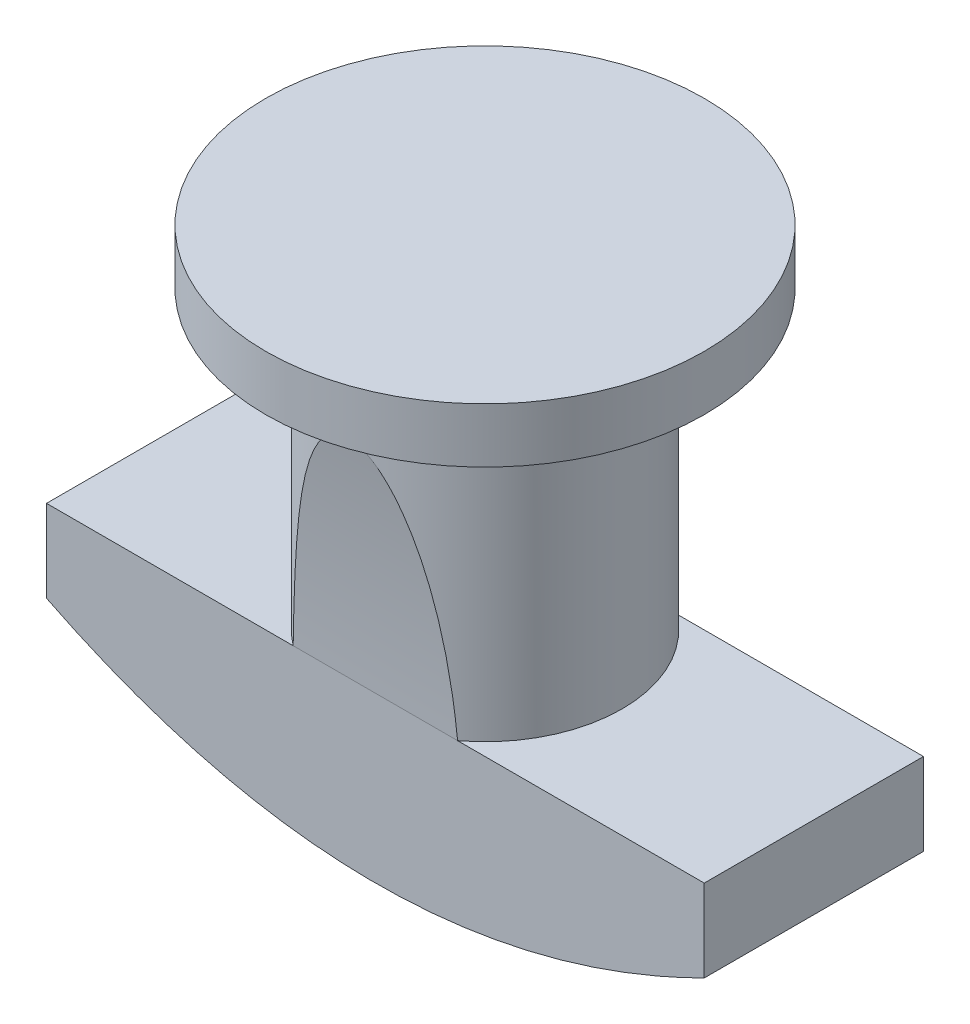
SolidWorks part; units mm, degrees
ref_plane "Front Plane" through (0, 0, 0) normal (0, 0, 1) x (1, 0, 0)
ref_plane "Top Plane" through (0, 0, 0) normal (0, 1, 0) x (1, 0, 0)
ref_plane "Right Plane" through (0, 0, 0) normal (1, 0, 0) x (0, 0, -1)
sketch "Sketch1" plane through (0, 0, 0) normal (0, 1, 0) x (1, 0, 0)
  circle A0 centre (0, 0) radius 4
  dimension "D1" = 8
extrude "Boss-Extrude1" add sketch "Sketch1" along normal blind 1
sketch "Sketch2" plane through (0, 0, 0) normal (0, -1, 0) x (-1, 0, 0)
  circle A0 centre (0, 0) radius 2.5
  dimension "D1" = 5
extrude "Boss-Extrude2" add sketch "Sketch2" along normal blind 5.4
sketch "Sketch3" plane through (0, -5.4, 0) normal (0, -1, 0) x (1, 0, 0)
  line L1 (-6, -2) -> (6, -2)
  line L2 (-6, -2) -> (-6, 2)
  line L3 (-6, 2) -> (6, 2)
  line L4 (6, -2) -> (6, 2)
  line L5 (-6, -2) -> (6, 2) construction
  line L6 (-6, 2) -> (6, -2) construction
  point P0 (0, 0)
  dimension "D1" = 12
  dimension "D2" = 4
extrude "Boss-Extrude3" add sketch "Sketch3" along normal blind 3
sketch "Sketch4" plane through (0, 0, -2) normal (0, 0, -1) x (-1, 0, 0)
  line L0 (6, -8.4) -> (6, -5.4) construction
  line L1 (6, -8.4) -> (-6, -8.4) construction
  line L2 (-6, -8.4) -> (-6, -5.4) construction
  line L3 (-6, -6.9) -> (-6.9278, -6.9)
  line L4 (-6.9278, -6.9) -> (-6.9278, -9.7902)
  line L5 (-6.9278, -9.7902) -> (7.4972, -9.7902)
  line L6 (7.4972, -9.7902) -> (7.4972, -6.8417)
  line L7 (6, -6.9) -> (7.4972, -6.8417)
  spline S0 degree 2 poles (6, -6.9) (0, -9.9) (-6, -6.9) knots 0 0 0 1 1 1
extrude "Cut-Extrude1" cut sketch "Sketch4" against normal through all both and the other way through all
sketch "Sketch5" plane through (0, 0, 0) normal (1, 0, 0) x (0, 0, -1)
  line L0 (2.5, -5.4) -> (2.5, 0) construction
  line L1 (2.5, -1.1105) -> (3.287, -1.1105)
  line L2 (3.287, -1.1105) -> (3.287, -6.2895)
  line L3 (3.287, -6.2895) -> (2, -5.4)
  line L6 (-3.287, -6.2895) -> (-2, -5.4)
  line L7 (-3.287, -1.1105) -> (-3.287, -6.2895)
  line L8 (-2.5, -1.1105) -> (-3.287, -1.1105)
  spline S0 degree 2 poles (2.5, -1.1105) (2.0947, -3.239) (2, -5.4) knots 0 0 0 1 1 1
  spline S1 degree 2 poles (-2.5, -1.1105) (-2.0947, -3.239) (-2, -5.4) knots 0 0 0 1 1 1
extrude "Cut-Extrude2" cut sketch "Sketch5" against normal through all both and the other way through all
